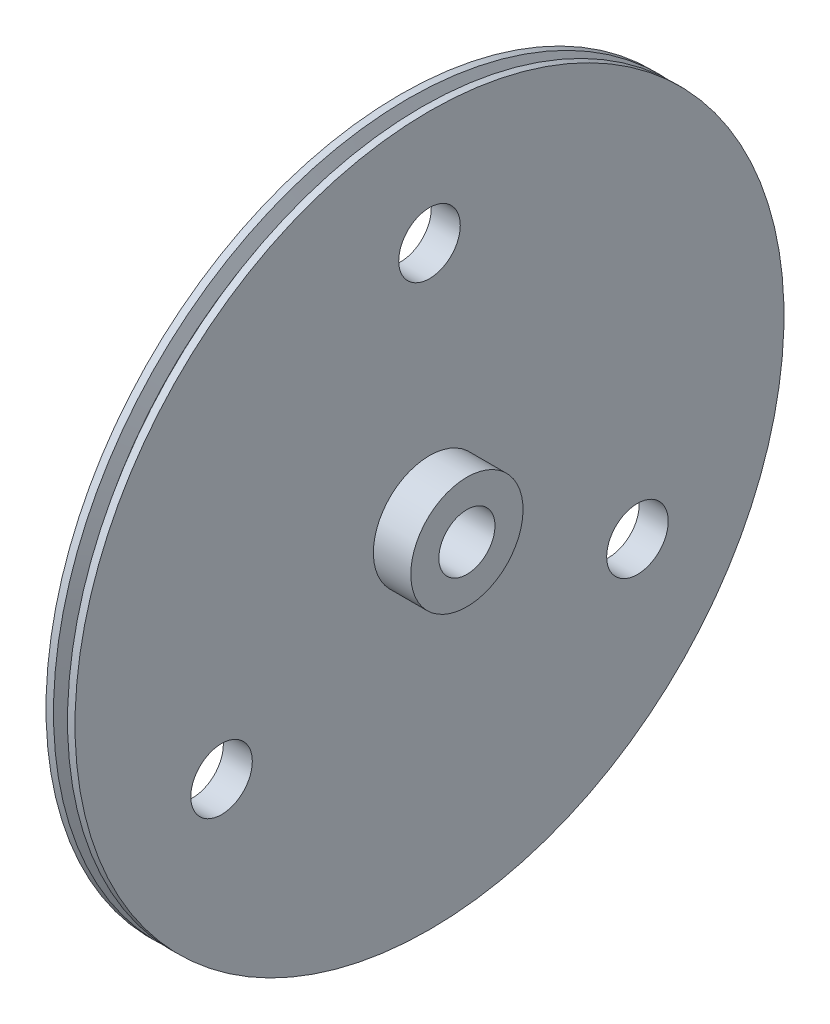
SolidWorks part; units mm, degrees
ref_plane "Front Plane" through (0, 0, 0) normal (0, 0, 1) x (1, 0, 0)
ref_plane "Top Plane" through (0, 0, 0) normal (0, 1, 0) x (1, 0, 0)
ref_plane "Right Plane" through (0, 0, 0) normal (1, 0, 0) x (0, 0, -1)
sketch "Sketch2" plane through (0, 0, 0) normal (0, 0, 1) x (1, 0, 0)
  line L0 (0, 0) -> (0, 240.665)
  line L6 (19.685, 240.665) -> (19.685, 38.1)
  line L7 (19.685, 38.1) -> (45.085, 38.1)
  line L8 (45.085, 38.1) -> (45.085, 0)
  line L9 (45.085, 0) -> (0, 0)
  line L10 (0, 240.665) -> (5.08, 240.665)
  line L12 (10.9037, 232.7275) -> (8.7813, 232.7275)
  line L14 (14.605, 240.665) -> (19.685, 240.665)
  line L15 (5.08, 240.665) -> (8.7813, 232.7275)
  line L16 (10.9037, 232.7275) -> (14.605, 240.665)
  point P4 (9.8425, 232.7275)
  dimension "D1" = 240.665
  dimension "D2" = 25
  dimension "D3" = 25
  dimension "D4" = 19.685
  dimension "D5" = 7.9375
  dimension "D6" = 9.525
  dimension "D7" = 5.08
  dimension "D8" = 25.4
  dimension "D9" = 38.1
revolve "Revolve1" add sketch "Sketch2" angle 360 about L9
sketch "Sketch3" plane through (45.085, 0, 0) normal (1, 0, 0) x (0, 0, -1)
  circle A0 centre (0, 0) radius 19.05
  dimension "D1" = 38.1
extrude "Cut-Extrude1" cut sketch "Sketch3" against normal through all
sketch "Sketch4" plane through (0, 0, 0) normal (-1, 0, 0) x (0, 0, 1)
  circle A0 centre (0, 0) radius 163.0228 construction
  circle A1 centre (0, 163.0228) radius 20.8935
  circle A2 centre (141.1819, -81.5114) radius 20.8935
  circle A3 centre (-141.1819, -81.5114) radius 20.8935
  point P11 (0, 0)
  dimension "D1" = 3
extrude "Cut-Extrude2" cut sketch "Sketch4" against normal through all
